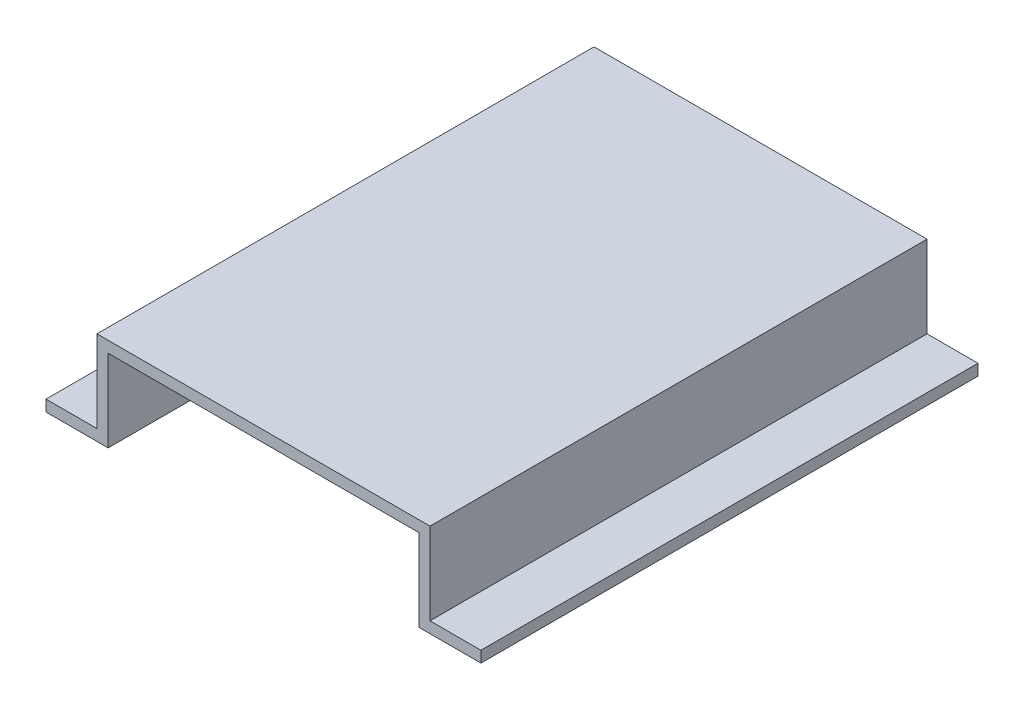
SolidWorks part; units mm, degrees
ref_plane "前视基准面" through (0, 0, 0) normal (0, 0, 1) x (1, 0, 0)
ref_plane "上视基准面" through (0, 0, 0) normal (0, 1, 0) x (1, 0, 0)
ref_plane "右视基准面" through (0, 0, 0) normal (1, 0, 0) x (0, 0, -1)
sketch "草图1" plane through (0, 0, 0) normal (0, 0, 1) x (1, 0, 0)
  line L0 (12.5, 0) -> (-12.5, 0)
  line L1 (-12.5, 0) -> (-12.5, -6.6)
  line L2 (-12.5, -6.6) -> (-17.5, -6.6)
  line L3 (0, 0) -> (0, -10.8972) construction
  line L4 (12.5, -6.6) -> (17.5, -6.6)
  line L5 (12.5, 0) -> (12.5, -6.6)
  line L6 (13.4, -5.7) -> (17.5, -5.7)
  line L7 (13.4, 0.9) -> (13.4, -5.7)
  line L8 (13.4, 0.9) -> (-13.4, 0.9)
  line L9 (-13.4, 0.9) -> (-13.4, -5.7)
  line L10 (-13.4, -5.7) -> (-17.5, -5.7)
  line L11 (17.5, -6.6) -> (17.5, -5.7)
  line L12 (-17.5, -6.6) -> (-17.5, -5.7)
  dimension "D1" = 35
  dimension "D2" = 25
  dimension "D3" = 6.6
  dimension "D4" = 0.9
extrude "凸台-拉伸1" add sketch "草图1" along normal blind 40
